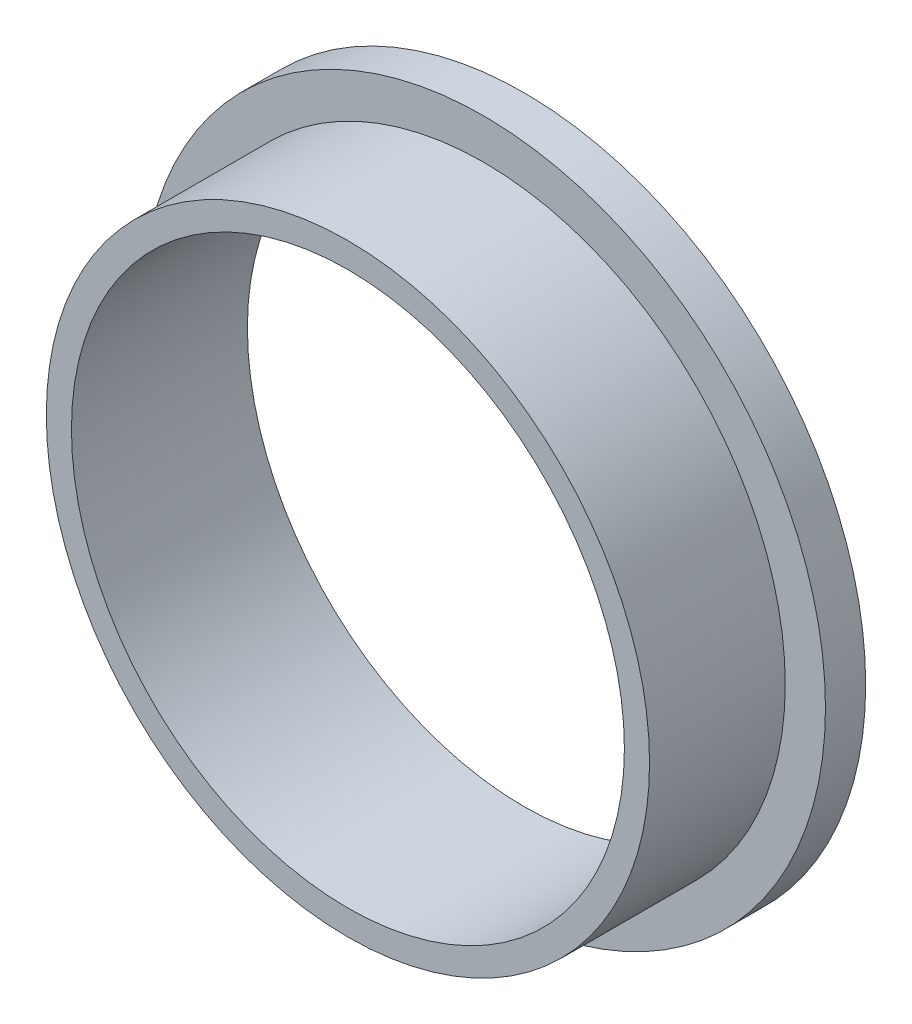
SolidWorks part; units mm, degrees
ref_plane "前视基准面" through (0, 0, 0) normal (0, 0, 1) x (1, 0, 0)
ref_plane "上视基准面" through (0, 0, 0) normal (0, 1, 0) x (1, 0, 0)
ref_plane "右视基准面" through (0, 0, 0) normal (1, 0, 0) x (0, 0, -1)
sketch "草图1" plane through (0, 0, 0) normal (0, 0, 1) x (1, 0, 0)
  circle A0 centre (0, 0) radius 5.5
  circle A1 centre (0, 0) radius 6
extrude "凸台-拉伸1" add sketch "草图1" along normal blind 3.5
sketch "草图2" plane through (0, 0, 0) normal (0, 0, 1) x (1, 0, 0)
  circle A0 centre (0, 0) radius 6.8
  circle A1 centre (0, 0) radius 5.5
extrude "凸台-拉伸2" add sketch "草图2" along normal blind 0.8
